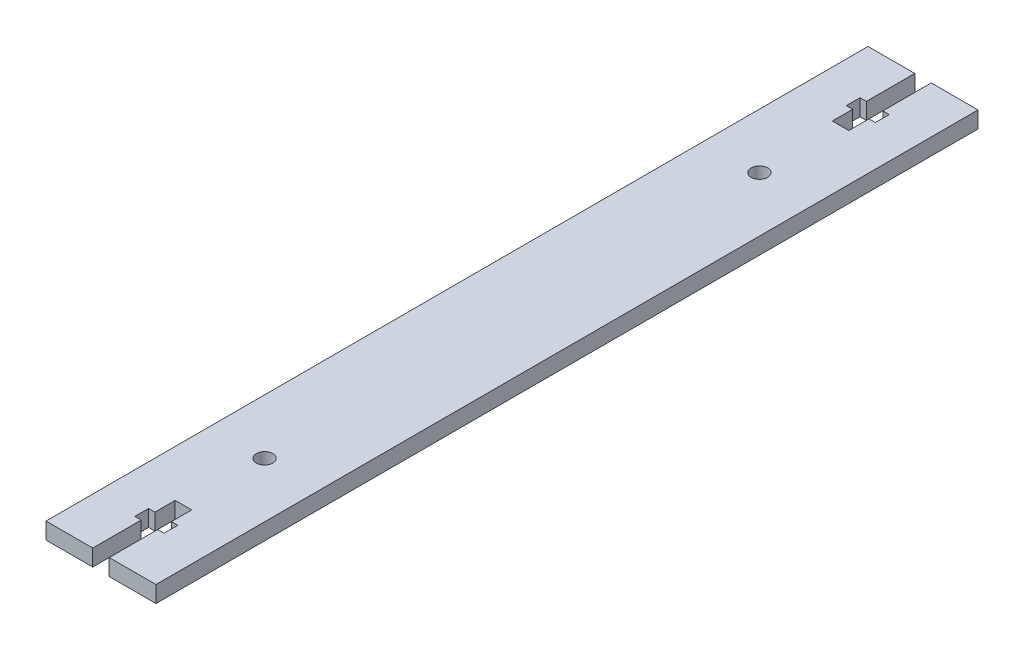
SolidWorks part; units mm, degrees
material "Mahogany"
ref_plane "Front Plane" through (0, 0, 0) normal (0, 0, 1) x (1, 0, 0)
ref_plane "Top Plane" through (0, 0, 0) normal (0, 1, 0) x (1, 0, 0)
ref_plane "Right Plane" through (0, 0, 0) normal (1, 0, 0) x (0, 0, -1)
sketch "Sketch2" plane through (0, 0, 0) normal (0, 0, 1) x (1, 0, 0)
  line L1 (-20, -3) -> (20, -3)
  line L2 (-20, -3) -> (-20, 3)
  line L3 (-20, 3) -> (20, 3)
  line L4 (20, -3) -> (20, 3)
  line L5 (-20, -3) -> (20, 3) construction
  line L6 (-20, 3) -> (20, -3) construction
  point P0 (0, 0)
  dimension "D1" = 40
  dimension "D2" = 6
extrude "Boss-Extrude2" add sketch "Sketch2" along normal blind 299
sketch "Sketch4" plane through (0, 3, 0) normal (0, 1, 0) x (1, 0, 0)
  circle A1 centre (0, -59.5) radius 3
  circle A2 centre (0, -239.5) radius 3
extrude "Cut-Extrude2" cut sketch "Sketch4" against normal mid plane 84
sketch "Sketch5" plane through (0, 3, 0) normal (0, 1, 0) x (1, 0, 0)
  line L0 (-3, -299) -> (3, -299)
  line L1 (20, -299) -> (-20, -299) construction
  line L2 (3, -299) -> (3, -281.3864)
  line L3 (3, -269) -> (-3, -269)
  line L4 (-3, -269) -> (-3, -276.3864)
  line L5 (-3, -281.3864) -> (-3, -299)
  line L10 (3, -281.3864) -> (5.3115, -281.3864)
  line L11 (3, -276.3864) -> (5.3115, -276.3864)
  line L12 (-5.3115, -281.3864) -> (-3, -281.3864)
  line L13 (-5.3115, -281.3864) -> (-5.3115, -276.3864)
  line L14 (-5.3115, -276.3864) -> (-3, -276.3864)
  line L15 (5.3115, -281.3864) -> (5.3115, -276.3864)
  line L18 (3, -276.3864) -> (3, -269)
  line L19 (20, -149.5) -> (-20, -149.5) construction
  line L20 (20, -299) -> (20, 0) construction
  line L21 (-20, -299) -> (-20, 0) construction
  point P5 (0, -299)
  point P7 (0, -279)
  point P14 (0, -279)
  dimension "D1" = 20
  dimension "D2" = 6
  dimension "D3" = 30
  dimension "D4" = 5
extrude "Cut-Extrude4" cut sketch "Sketch5" against normal mid plane 84
ref_plane "Plane1" through (0, 0, 149.5) normal (0, 0, 1) x (1, 0, 0)
mirror "Mirror2" about plane through (0, 0, 149.5) normal (0, 0, 1) of "Cut-Extrude4"
